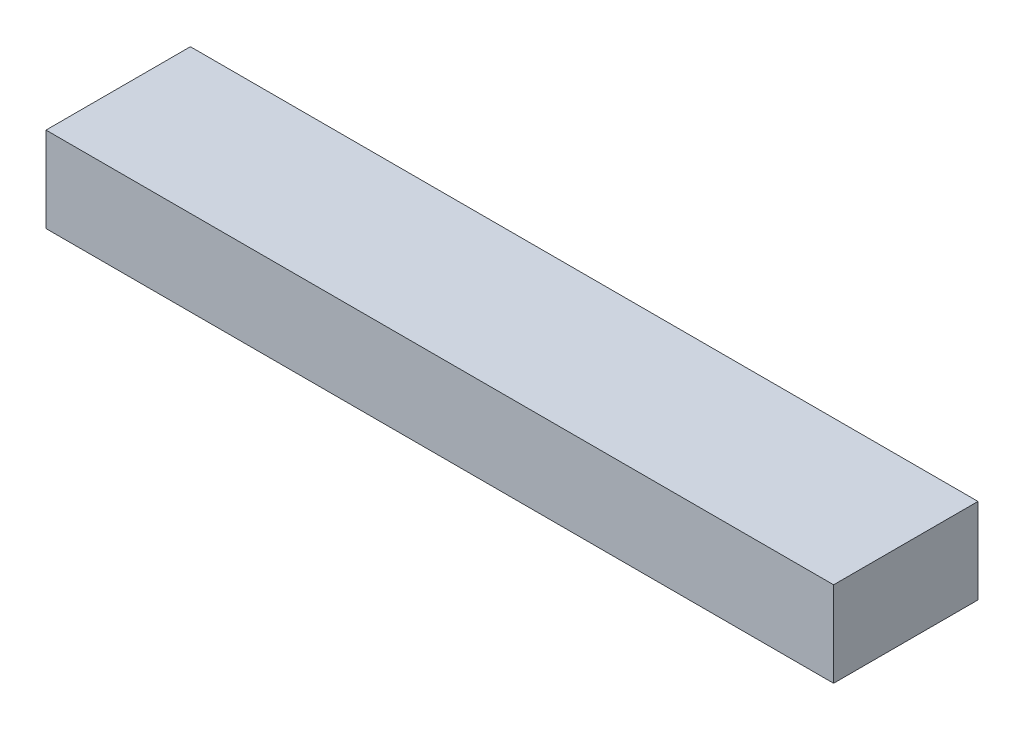
SolidWorks part; units mm, degrees
material "黄铜"
ref_plane "前视基准面" through (0, 0, 0) normal (0, 0, 1) x (1, 0, 0)
ref_plane "上视基准面" through (0, 0, 0) normal (0, 1, 0) x (1, 0, 0)
ref_plane "右视基准面" through (0, 0, 0) normal (1, 0, 0) x (0, 0, -1)
sketch "草图1" plane through (0, 0, 0) normal (0, 1, 0) x (1, 0, 0)
  line L1 (-58.0825, 33.1134) -> (61.9175, 33.1134)
  line L2 (-58.0825, 33.1134) -> (-58.0825, 11.1134)
  line L3 (-58.0825, 11.1134) -> (61.9175, 11.1134)
  line L4 (61.9175, 33.1134) -> (61.9175, 11.1134)
  circle A0 centre (-53.0825, 29.6134) radius 2
  circle A1 centre (56.9175, 29.6134) radius 2
  dimension "D5" = 4
  dimension "D8" = 4
  dimension "D1" = 22
  dimension "D2" = 120
  dimension "D3" = 5
  dimension "D4" = 3.5
  dimension "D6" = 3.5
  dimension "D7" = 5
extrude "凸台-拉伸1" add sketch "草图1" along normal blind 13 contours L1 L4 L3 L2
